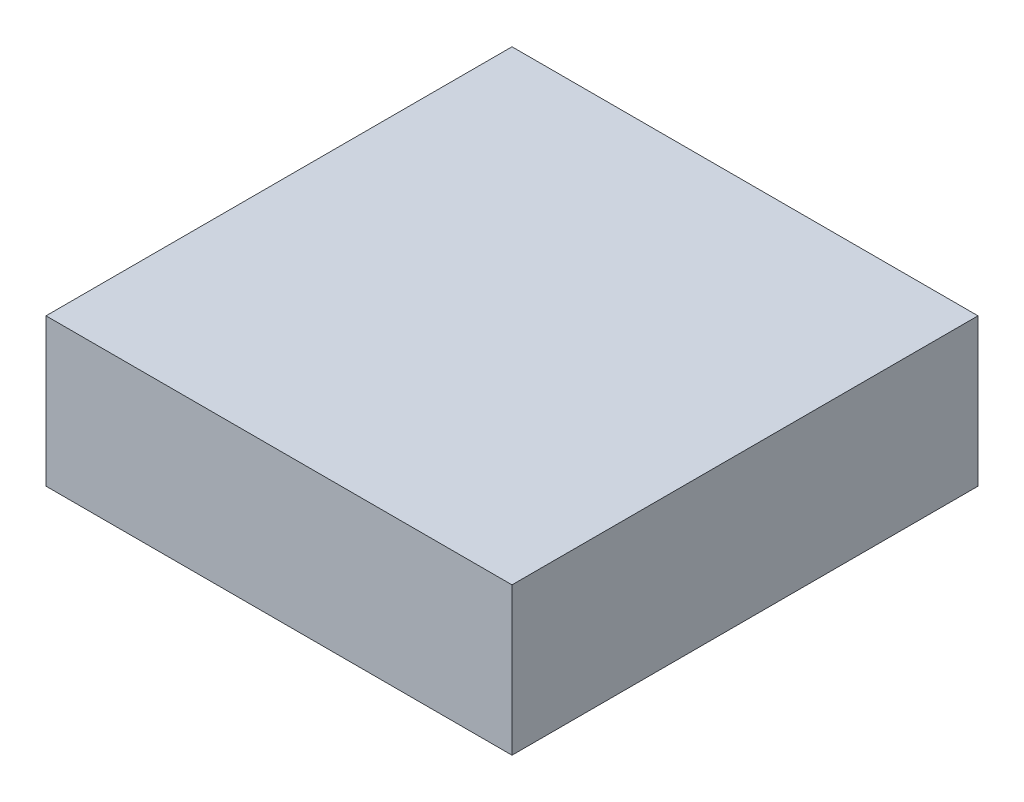
SolidWorks part; units mm, degrees
ref_plane "Front Plane" through (0, 0, 0) normal (0, 0, 1) x (1, 0, 0)
ref_plane "Top Plane" through (0, 0, 0) normal (0, 1, 0) x (1, 0, 0)
ref_plane "Right Plane" through (0, 0, 0) normal (1, 0, 0) x (0, 0, -1)
sketch "Sketch1" plane through (0, 0, 0) normal (0, 1, 0) x (1, 0, 0)
  line L1 (0, 0) -> (120, 0)
  line L2 (0, 0) -> (0, 120)
  line L3 (0, 120) -> (120, 120)
  line L4 (120, 0) -> (120, 120)
  dimension "D1" = 120
extrude "Boss-Extrude1" add sketch "Sketch1" along normal blind 38
